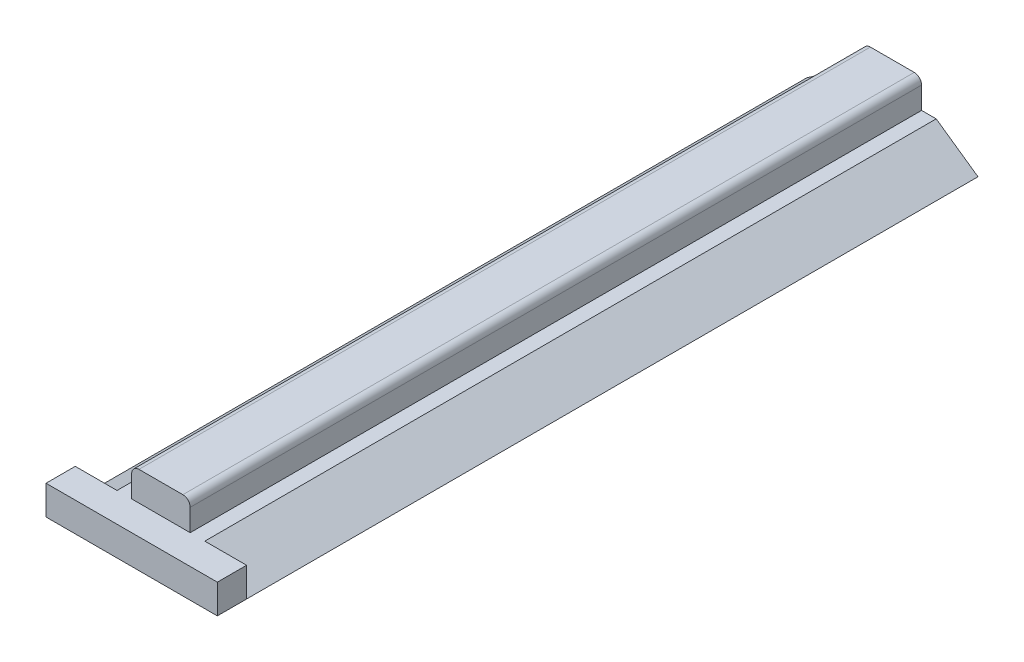
SolidWorks part; units mm, degrees
ref_plane "Front" through (0, 0, 0) normal (0, 0, 1) x (1, 0, 0)
ref_plane "Top" through (0, 0, 0) normal (0, 1, 0) x (1, 0, 0)
ref_plane "Right" through (0, 0, 0) normal (1, 0, 0) x (0, 0, -1)
sketch "Sketch1" plane through (0, 0, 0) normal (0, 0, 1) x (1, 0, 0)
  line L0 (0, 0) -> (-1.4281, -1)
  line L1 (-1.4281, -1) -> (4.4281, -1)
  line L2 (4.4281, -1) -> (3, 0)
  line L3 (3, 0) -> (0, 0)
  dimension "D1" = 3
  dimension "D2" = 35
  dimension "D3" = 35
  dimension "D4" = 1
extrude "Boss-Extrude1" add sketch "Sketch1" along normal blind 25
sketch "Sketch2" plane through (0, 0, 25) normal (0, 0, 1) x (1, 0, 0)
  line L0 (4.4281, -1) -> (3, 0) construction
  line L1 (-1.4281, -1) -> (4.4281, -1)
  line L2 (-1.4281, -1) -> (-1.4281, 0)
  line L3 (-1.4281, 0) -> (4.4281, 0)
  line L4 (4.4281, -1) -> (4.4281, 0)
  line L5 (-1.4281, -1) -> (4.4281, -1) construction
  line L6 (3, 0) -> (0, 0) construction
extrude "Boss-Extrude2" add sketch "Sketch2" along normal blind 1
sketch "Sketch3" plane through (0, 0, 0) normal (0, 1, 0) x (1, 0, 0)
  line L0 (3, 0) -> (0, 0) construction
  line L1 (0.5, 0) -> (2.5, 0)
  line L2 (0.5, 0) -> (0.5, -25)
  line L3 (0.5, -25) -> (2.5, -25)
  line L4 (2.5, 0) -> (2.5, -25)
  line L5 (4.4281, -25) -> (3, -25) construction
  line L6 (1.5, -25) -> (1.5, -26) construction
  line L7 (4.4281, -26) -> (-1.4281, -26) construction
  dimension "D1" = 2
extrude "Boss-Extrude3" add sketch "Sketch3" along normal blind 1
fillet "Fillet1" radius 0.25 2 edges at (2.5, 1, 12.5) (0.5, 1, 12.5)
